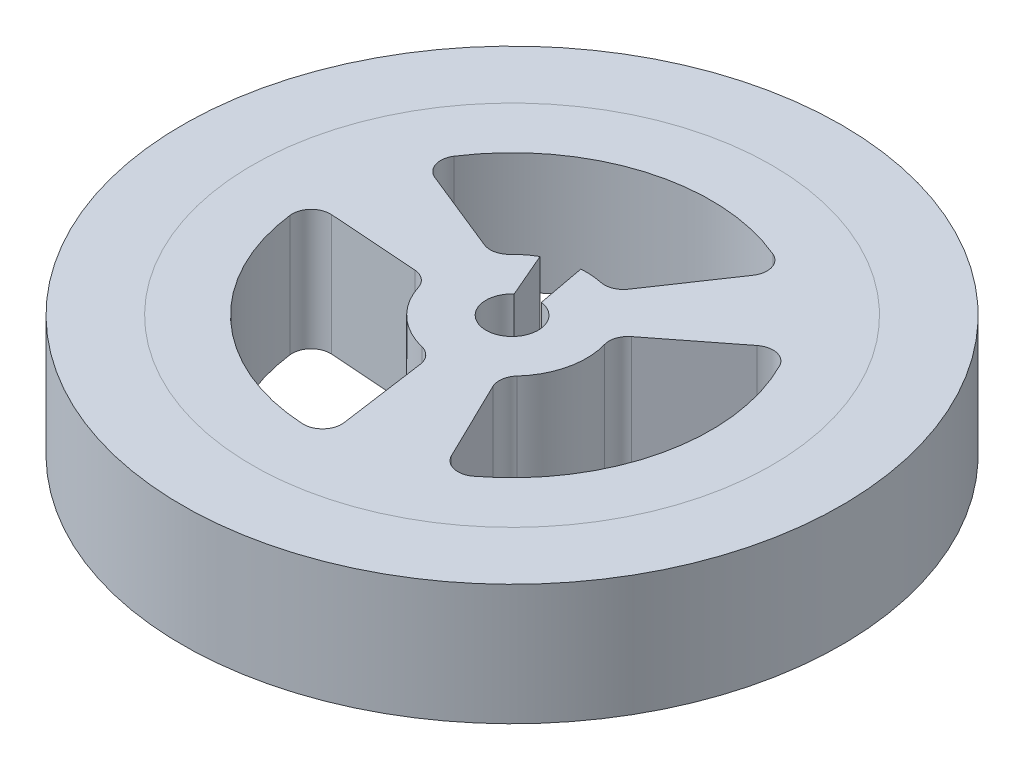
SolidWorks part; units mm, degrees
ref_plane "Front Plane" through (0, 0, 0) normal (0, 0, 1) x (1, 0, 0)
ref_plane "Top Plane" through (0, 0, 0) normal (0, 1, 0) x (1, 0, 0)
ref_plane "Right Plane" through (0, 0, 0) normal (1, 0, 0) x (0, 0, -1)
sketch "Sketch1" plane through (0, 0, 0) normal (0, 1, 0) x (1, 0, 0)
  circle A0 centre (0, 0) radius 13.595
  circle A1 centre (0, 0) radius 10.415
extrude "Boss-Extrude1" add sketch "Sketch1" along normal blind 6.32
sketch "Sketch2" plane through (0, 0, 0) normal (0, 0, 1) x (1, 0, 0)
  line L1 (0, 0) -> (0, 8.5287)
  line L5 (-13.595, 6.32) -> (-13.595, 0) construction
  line L7 (-13.595, 4.75) -> (-15.495, 4.75)
  line L8 (-15.495, 4.75) -> (-15.495, 1.57)
  line L9 (-15.495, 1.57) -> (-13.595, 1.57)
  line L10 (-13.595, 4.75) -> (-13.595, 1.57)
revolve "Revolve1" add sketch "Sketch2" angle 360 about L1
sketch "Sketch3" plane through (0, 6.32, 0) normal (0, 1, 0) x (1, 0, 0)
  circle A0 centre (0, 0) radius 3.9
extrude "Boss-Extrude2" add sketch "Sketch3" against normal up to surface (6.32 mm away) separate body up to face at (0, 0, 13.595)
sketch "Sketch4" plane through (0, 0, 0) normal (0, -1, 0) x (1, 0, 0)
  circle A0 centre (0, 0) radius 3.9 construction
  circle A1 centre (0, 0) radius 3.9
extrude "Boss-Extrude3" add sketch "Sketch4" along normal blind 2.31
sketch "Sketch5" plane through (0, 6.32, 0) normal (0, 1, 0) x (1, 0, 0)
  circle A0 centre (0, 0) radius 1.365
extrude "Cut-Extrude1" cut sketch "Sketch5" against normal up to surface (8.63 mm away) up to face at (0, -2.31, -3.9)
sketch "Sketch6" plane through (0, 6.32, 0) normal (0, 1, 0) x (1, 0, 0)
  line L5 (5.1342, 9.0616) -> (1.458, 3.6172)
  line L6 (8.6865, 5.746) -> (3.5096, 1.7009)
  circle A2 centre (0, 0) radius 10.415 construction
  circle A3 centre (0, 0) radius 3.9 construction
  arc A4 (3.5096, 1.7009) -> (1.458, 3.6172) centre (0, 0) ccw
  arc A5 (8.6865, 5.746) -> (5.1342, 9.0616) centre (0, 0) ccw
extrude "Boss-Extrude4" add sketch "Sketch6" against normal up to surface (6.32 mm away) up to face at (0, 0, 13.595)
pattern_circular "CirPattern2" count 3 over 360 about axis through (0, 0, 0) along (0, 1, 0) of "Boss-Extrude4"
fillet "Fillet2" radius 1 1 edges at (0.633, 3.16, 10.3957)
fillet "Fillet3" radius 1 11 edges at (5.1342, 3.16, -9.0616) (1.458, 3.16, -3.6172) (3.5096, 3.16, -1.7009) (8.6865, 3.16, -5.746) (5.2805, 3.16, 8.9771) (2.4036, 3.16, 3.0713) (-3.2278, 3.16, -2.1889) (-9.3195, 3.16, -4.6497) (-10.4147, 3.16, 0.0845) (-3.8616, 3.16, 0.546) (-0.2818, 3.16, 3.8898)
sketch "Sketch7" plane through (0, 6.32, 0) normal (0, 1, 0) x (1, 0, 0)
  line L2 (-1.9279, 3.3902) -> (-0.9074, 1.0197)
  line L4 (0.1841, 1.3525) -> (-0.2917, 3.8891)
  arc A0 (0.8292, 3.8108) -> (-2.8145, 2.6998) centre (0, 0) ccw construction
  arc A1 (-0.2917, 3.8891) -> (-1.9279, 3.3902) centre (0, 0) ccw
  circle A2 centre (0, 0) radius 1.365 construction
  arc A3 (0.1841, 1.3525) -> (-0.9074, 1.0197) centre (0, 0) ccw
extrude "Cut-Extrude2" cut sketch "Sketch7" against normal blind 25.31
sketch "Sketch8" plane through (0, 0, 0) normal (0, 0, 1) x (1, 0, 0)
  line L1 (-13.595, 4.75) -> (-15.495, 4.75)
  line L3 (-13.595, 1.57) -> (-15.495, 1.57)
  line L5 (0, 0) -> (0, 9.3973)
  line L7 (-13.595, 6.32) -> (-17.2423, 6.32)
  line L9 (-17.2423, 6.32) -> (-17.2423, 0)
  line L10 (-13.595, 6.32) -> (-13.595, 4.75)
  line L11 (-15.495, 4.75) -> (-15.495, 1.57)
  line L12 (-13.595, 1.57) -> (-13.595, 0)
  line L13 (-17.2423, 0) -> (-13.595, 0)
revolve "Revolve4" add sketch "Sketch8" angle 360 about L5
